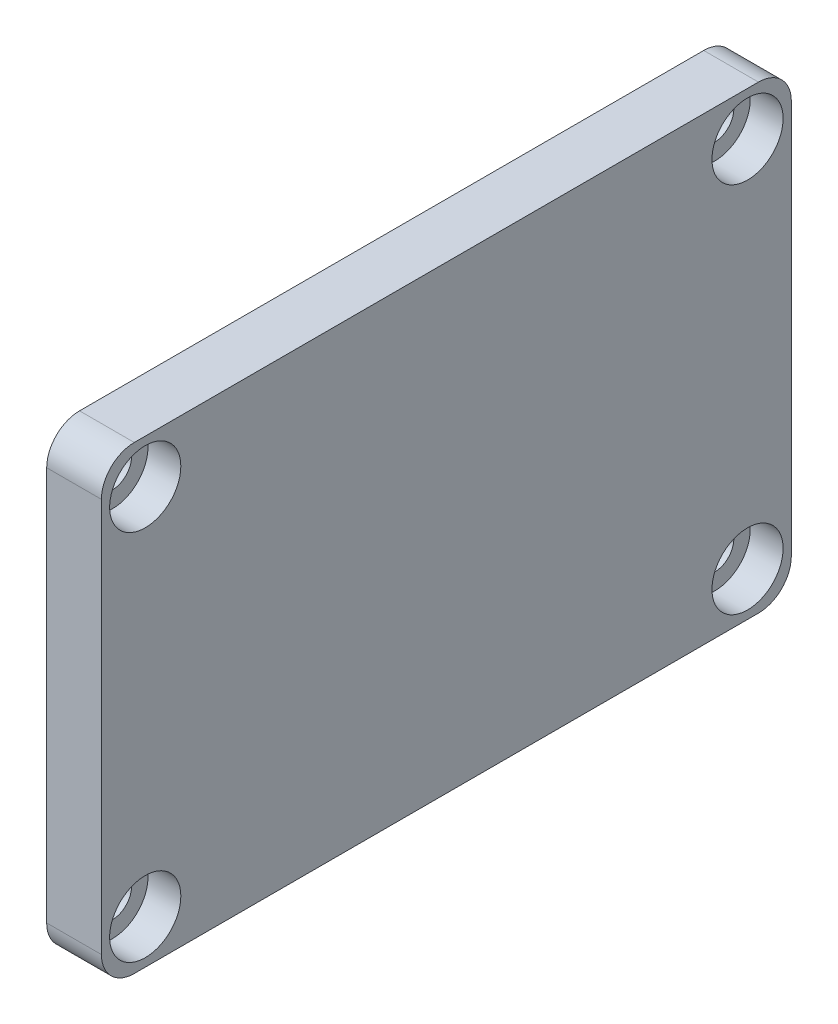
SolidWorks part; units mm, degrees
ref_plane "Front Plane" through (0, 0, 0) normal (1, 0, 0) x (0, 1, 0)
ref_plane "Top Plane" through (0, 0, 0) normal (0, 0, 1) x (0, 1, 0)
ref_plane "Right Plane" through (0, 0, 0) normal (0, 1, 0) x (-1, 0, 0)
sketch "Sketch1" plane through (0, 0, 0) normal (1, 0, 0) x (0, 1, 0)
  line L1 (-18, -31.5) -> (18, -31.5)
  line L2 (-21, -28.5) -> (-21, 28.5)
  line L3 (-18, 31.5) -> (18, 31.5)
  line L4 (21, -28.5) -> (21, 28.5)
  line L5 (-21, -31.5) -> (21, 31.5) construction
  line L6 (-21, 31.5) -> (21, -31.5) construction
  arc A0 (21, 28.5) -> (18, 31.5) centre (18, 28.5) ccw
  arc A1 (18, -31.5) -> (21, -28.5) centre (18, -28.5) ccw
  arc A2 (-18, -31.5) -> (-21, -28.5) centre (-18, -28.5) cw
  arc A3 (-21, 28.5) -> (-18, 31.5) centre (-18, 28.5) cw
  point P0 (0, 0)
  dimension "D3" = 3
  dimension "D1" = 42
  dimension "D2" = 63
extrude "Boss-Extrude1" add sketch "Sketch1" along normal blind 5
sketch "Sketch2" plane through (5, 0, 0) normal (1, 0, 0) x (0, 1, 0)
  line L2 (-21, 31.5) -> (21, 31.5) construction
  line L3 (-21, 31.5) -> (-21, -31.5) construction
  line L4 (-21, -31.5) -> (21, -31.5) construction
  line L5 (21, 31.5) -> (21, -31.5) construction
  line L9 (18, 31.5) -> (-18, 31.5) construction
  line L10 (-17, 27.5) -> (-17, -27.5) construction
  line L11 (-17, -27.5) -> (17, -27.5) construction
  line L12 (17, 27.5) -> (17, -27.5) construction
  line L13 (-17, 27.5) -> (17, 27.5) construction
  line L14 (-21, 28.5) -> (-21, -28.5) construction
  line L15 (21, -28.5) -> (21, 28.5) construction
  line L16 (-18, -31.5) -> (18, -31.5) construction
  circle A0 centre (-17, 27.5) radius 1.75
  circle A1 centre (17, 27.5) radius 1.75
  circle A2 centre (17, -27.5) radius 1.75
  circle A3 centre (-17, -27.5) radius 1.75
  dimension "D2" = 3.5
  dimension "D1" = 4
extrude "Cut-Extrude1" cut sketch "Sketch2" against normal through all
sketch "Sketch3" plane through (5, 0, 0) normal (1, 0, 0) x (0, 1, 0)
  circle A1 centre (17, 27.5) radius 3.25
  circle A2 centre (-17, 27.5) radius 3.25
  circle A3 centre (-17, 27.5) radius 3.25
  circle A4 centre (17, -27.5) radius 3.25
  circle A5 centre (-17, -27.5) radius 3.25
  dimension "D1" = 1.5
extrude "Cut-Extrude2" cut sketch "Sketch3" against normal blind 3
